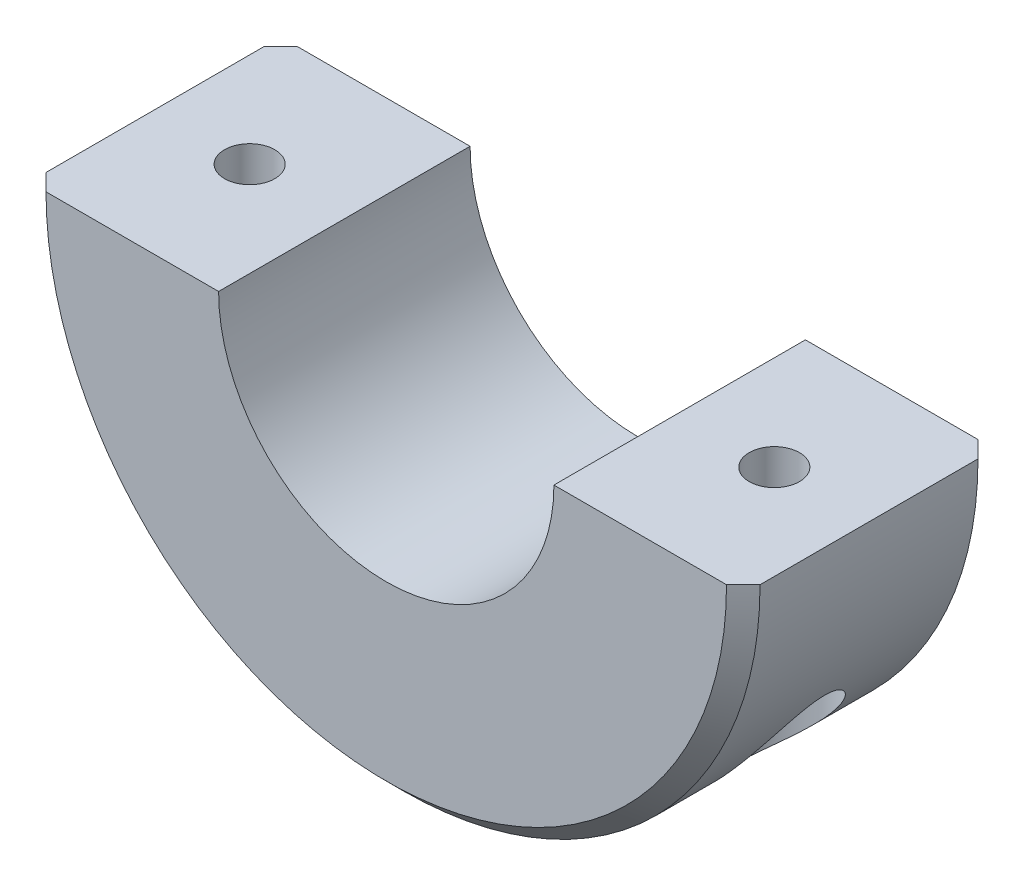
SolidWorks part; units mm, degrees
ref_plane "前视基准面" through (0, 0, 0) normal (0, 0, 1) x (1, 0, 0)
ref_plane "上视基准面" through (0, 0, 0) normal (0, 1, 0) x (1, 0, 0)
ref_plane "右视基准面" through (0, 0, 0) normal (1, 0, 0) x (0, 0, -1)
sketch "草图1" plane through (0, 0, 0) normal (0, 0, 1) x (1, 0, 0)
  line L0 (-21.295, 0) -> (-10, 0)
  line L1 (10, 0) -> (21.295, 0)
  arc A0 (-10, 0) -> (10, 0) centre (0, 0) ccw
  arc A1 (-21.295, 0) -> (21.295, 0) centre (0, 0) ccw
extrude "凸台-拉伸1" add sketch "草图1" along normal blind 15
sketch "草图2" plane through (0, 0, 0) normal (0, 1, 0) x (1, 0, 0)
  circle A0 centre (-15.6475, -7.5) radius 1.5
  circle A1 centre (15.6475, -7.5) radius 1.5
extrude "切除-拉伸1" cut sketch "草图2" against normal blind 34
ref_plane "基准面1" through (0, -25, 0) normal (0, 1, 0) x (1, 0, 0)
sketch "草图3" plane through (0, -25, 0) normal (0, 1, 0) x (1, 0, 0)
  circle A0 centre (-15.6475, -7.5) radius 3
  circle A1 centre (15.6475, -7.5) radius 3
extrude "切除-拉伸2" cut sketch "草图3" along normal blind 18
chamfer "倒角1" distance 1 angle 45 2 edges at (0, -21.295, 15) (0, -21.295, 0)
